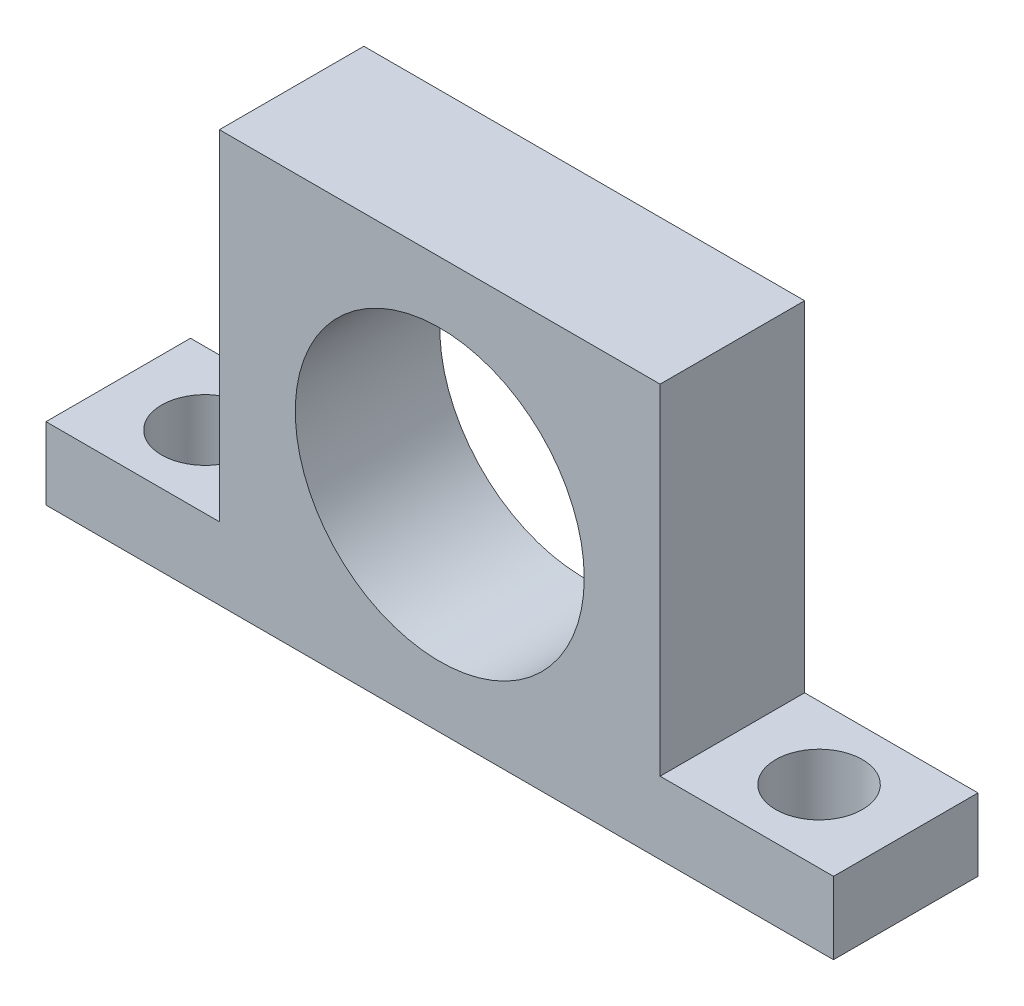
SolidWorks part; units mm, degrees
ref_plane "前视基准面" through (0, 0, 0) normal (0, 0, 1) x (1, 0, 0)
ref_plane "上视基准面" through (0, 0, 0) normal (0, 1, 0) x (1, 0, 0)
ref_plane "右视基准面" through (0, 0, 0) normal (1, 0, 0) x (0, 0, -1)
other "Configuration Table"
sketch "草图1" plane through (0, 0, 0) normal (0, 0, 1) x (1, 0, 0)
  line L0 (2.1, -6.95) -> (2.1, -21.2) construction
  line L1 (-25.15, 7.3) -> (29.35, 7.3)
  line L2 (-25.15, 7.3) -> (-25.15, -21.2)
  line L3 (-25.15, -21.2) -> (29.35, -21.2)
  line L4 (29.35, 7.3) -> (29.35, -21.2)
  line L7 (-25.15, 7.3) -> (-13.15, 7.3)
  line L8 (-25.15, 7.3) -> (-25.15, -16.2)
  line L9 (-25.15, -16.2) -> (-13.15, -16.2)
  line L10 (-13.15, 7.3) -> (-13.15, -16.2)
  line L11 (29.35, -16.2) -> (17.35, -16.2)
  line L12 (17.35, 7.3) -> (17.35, -16.2)
  line L13 (29.35, 7.3) -> (17.35, 7.3)
  line L14 (29.35, 7.3) -> (29.35, -16.2)
  circle A0 centre (2.1, -6.95) radius 4
  circle A1 centre (2.1, -6.95) radius 10
  point P0 (0, 0)
  dimension "D6" = 8
  dimension "D7" = 20
  dimension "D1" = 54.5
  dimension "D2" = 5
  dimension "D3" = 30.5
  dimension "D4" = 14.25
  dimension "D5" = 28.5
extrude "凸台-拉伸1" add sketch "草图1" along normal blind 10
sketch "草图2" plane through (0, 7.3, 0) normal (0, 1, 0) x (1, 0, 0)
  line L0 (-25.15, -5) -> (-13.15, -5) construction
  line L1 (-25.15, -10) -> (-25.15, 0) construction
  line L2 (-13.15, -10) -> (-13.15, 0) construction
  line L3 (2.1, 0) -> (2.1, -10) construction
  line L4 (-13.15, -10) -> (17.35, -10) construction
  circle A0 centre (-19.15, -5) radius 3
  circle A2 centre (23.35, -5) radius 3
  dimension "D1" = 6
extrude "切除-拉伸1" cut sketch "草图2" against normal through all
